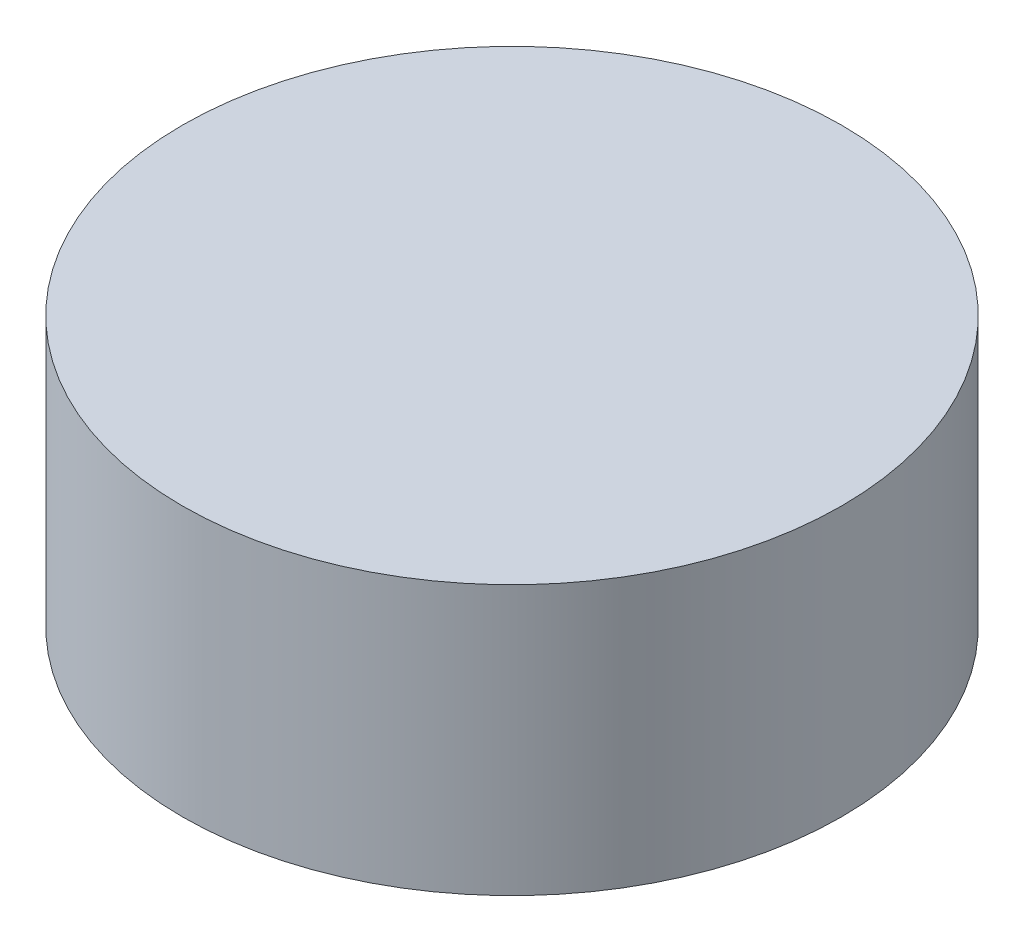
SolidWorks part; units mm, degrees
material "6061-T6 (SS)"
ref_plane "Alzado" through (0, 0, 0) normal (0, 0, 1) x (1, 0, 0)
ref_plane "Planta" through (0, 0, 0) normal (0, 1, 0) x (1, 0, 0)
ref_plane "Vista lateral" through (0, 0, 0) normal (1, 0, 0) x (0, 0, -1)
sketch "Croquis1" plane through (0, 0, 0) normal (0, 1, 0) x (1, 0, 0)
  circle A0 centre (0, 0) radius 3
  dimension "D1" = 6
extrude "Saliente-Extruir1" add sketch "Croquis1" along normal blind 2.45
